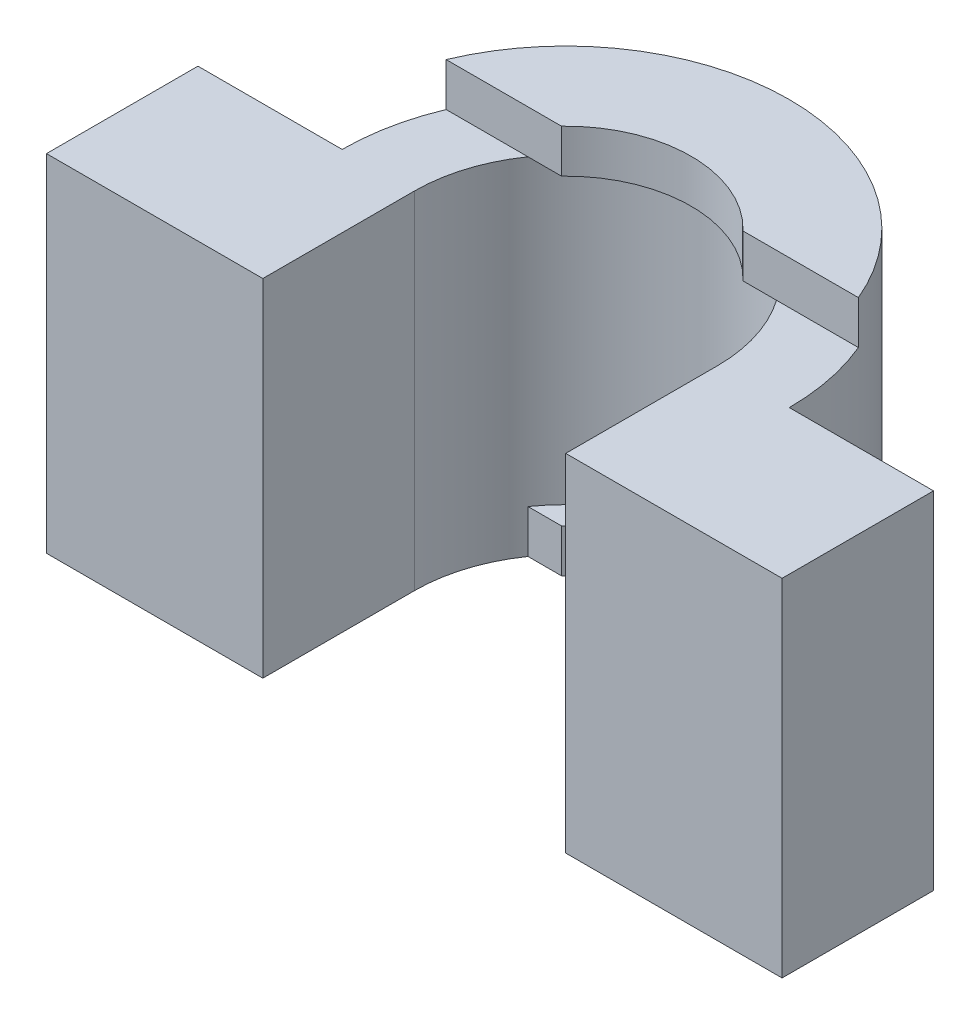
SolidWorks part; units mm, degrees
ref_plane "Plan de face" through (0, 0, 0) normal (0, 0, 1) x (1, 0, 0)
ref_plane "Plan de dessus" through (0, 0, 0) normal (0, 1, 0) x (1, 0, 0)
ref_plane "Plan de droite" through (0, 0, 0) normal (1, 0, 0) x (0, 0, -1)
sketch "Esquisse1" plane through (0, 0, 0) normal (0, 1, 0) x (1, 0, 0)
  line L0 (6.6429, 1.4286) -> (6.6429, -9.0714)
  line L3 (-19.3571, 1.4286) -> (-29.3571, 1.4286)
  line L4 (11.6429, 1.4286) -> (21.6429, 1.4286)
  line L5 (-14.3571, 1.4286) -> (-14.3571, -9.0714)
  line L6 (-29.3571, 1.4286) -> (-19.3571, 1.4286)
  line L7 (-29.3571, 1.4286) -> (-29.3571, -9.0714)
  line L8 (-29.3571, -9.0714) -> (-19.3571, -9.0714)
  line L9 (-14.3571, -9.0714) -> (-19.3571, -9.0714)
  line L10 (11.6429, 1.4286) -> (21.6429, 1.4286)
  line L11 (6.6429, -9.0714) -> (11.6429, -9.0714)
  line L12 (11.6429, -9.0714) -> (21.6429, -9.0714)
  line L13 (21.6429, 1.4286) -> (21.6429, -9.0714)
  arc A0 (-14.3571, 1.4286) -> (6.6429, 1.4286) centre (-3.8571, 1.4286) cw
  arc A1 (-19.3571, 1.4286) -> (11.6429, 1.4286) centre (-3.8571, 1.4286) cw
  dimension "D1" = 21
  dimension "D2" = 5
  dimension "D3" = 5
  dimension "D4" = 10
  dimension "D5" = 10
  dimension "D6" = 10.5
  dimension "D7" = 10.5
extrude "Boss.-Extru.1" add sketch "Esquisse1" along normal blind 21 contours A1 L3 L7 L8 L9 L5 A0 L0 L11 L12 L13 L4
sketch "Esquisse2" plane through (0, 21, 0) normal (0, 1, 0) x (1, 0, 0)
  line L0 (-18.1487, 7.4286) -> (-10.1487, 7.4286)
  line L1 (2.4345, 7.4286) -> (10.4345, 7.4286)
  arc A0 (-18.1487, 7.4286) -> (10.4345, 7.4286) centre (-3.8571, 1.4286) cw
  arc A1 (11.6429, 1.4286) -> (-19.3571, 1.4286) centre (-3.8571, 1.4286) ccw construction
  arc A2 (-10.1487, 7.4286) -> (2.4345, 7.4286) centre (-3.8571, 1.4286) cw
  arc A3 (6.6429, 1.4286) -> (-14.3571, 1.4286) centre (-3.8571, 1.4286) ccw construction
  dimension "D1" = 0
  dimension "D5" = 0
  dimension "D2" = 6
  dimension "D4" = 8
extrude "Boss.-Extru.2" add sketch "Esquisse2" along normal blind 3
sketch "Esquisse3" plane through (0, 0, 0) normal (0, -1, 0) x (-1, 0, 0)
  line L0 (-10.4345, 7.4286) -> (-2.4345, 7.4286)
  line L1 (10.1487, 7.4286) -> (18.1487, 7.4286)
  arc A0 (-10.4345, 7.4286) -> (18.1487, 7.4286) centre (3.8571, 1.4286) cw
  arc A1 (19.3571, 1.4286) -> (-11.6429, 1.4286) centre (3.8571, 1.4286) ccw construction
  arc A2 (-2.4345, 7.4286) -> (10.1487, 7.4286) centre (3.8571, 1.4286) cw
  arc A4 (14.3571, 1.4286) -> (-6.6429, 1.4286) centre (3.8571, 1.4286) ccw construction
  dimension "D1" = 6
  dimension "D2" = 0
  dimension "D4" = 0
  dimension "D3" = 8
extrude "Boss.-Extru.3" add sketch "Esquisse3" along normal blind 3
sketch "Esquisse5" plane through (0, 0, 0) normal (0, -1, 0) x (1, 0, 0)
  line L5 (-18.1487, -7.4286) -> (-12.474, -7.4286)
  line L6 (-14.3571, -1.4286) -> (-14.3571, 9.0714)
  line L7 (-14.3571, 9.0714) -> (-29.3571, 9.0714)
  line L8 (-29.3571, 9.0714) -> (-29.3571, -1.4286)
  line L9 (-29.3571, -1.4286) -> (-19.3571, -1.4286)
  line L10 (-18.1487, -7.4286) -> (-12.474, -7.4286)
  line L11 (-14.3571, -1.4286) -> (-14.3571, 9.0714)
  line L12 (-14.3571, 9.0714) -> (-29.3571, 9.0714)
  line L13 (-29.3571, 9.0714) -> (-29.3571, -1.4286)
  line L14 (-29.3571, -1.4286) -> (-19.3571, -1.4286)
  line L15 (4.7597, -7.4286) -> (10.4345, -7.4286)
  line L16 (11.6429, -1.4286) -> (21.6429, -1.4286)
  line L17 (21.6429, -1.4286) -> (21.6429, 9.0714)
  line L18 (21.6429, 9.0714) -> (6.6429, 9.0714)
  line L19 (6.6429, 9.0714) -> (6.6429, -1.4286)
  line L20 (4.7597, -7.4286) -> (10.4345, -7.4286)
  line L21 (11.6429, -1.4286) -> (21.6429, -1.4286)
  line L22 (21.6429, -1.4286) -> (21.6429, 9.0714)
  line L23 (21.6429, 9.0714) -> (6.6429, 9.0714)
  line L24 (6.6429, 9.0714) -> (6.6429, -1.4286)
  arc A2 (-14.3571, -1.4286) -> (-12.474, -7.4286) centre (-3.8571, -1.4286) ccw
  arc A3 (-19.3571, -1.4286) -> (-18.1487, -7.4286) centre (-3.8571, -1.4286) ccw
  arc A4 (-14.3571, -1.4286) -> (-12.474, -7.4286) centre (-3.8571, -1.4286) ccw
  arc A5 (-19.3571, -1.4286) -> (-18.1487, -7.4286) centre (-3.8571, -1.4286) ccw
  arc A6 (10.4345, -7.4286) -> (11.6429, -1.4286) centre (-3.8571, -1.4286) ccw
  arc A7 (4.7597, -7.4286) -> (6.6429, -1.4286) centre (-3.8571, -1.4286) ccw
  arc A8 (10.4345, -7.4286) -> (11.6429, -1.4286) centre (-3.8571, -1.4286) ccw
  arc A9 (4.7597, -7.4286) -> (6.6429, -1.4286) centre (-3.8571, -1.4286) ccw
  dimension "D1" = 0
  dimension "D2" = 0
extrude "Boss.-Extru.5" add sketch "Esquisse5" along normal blind 3
